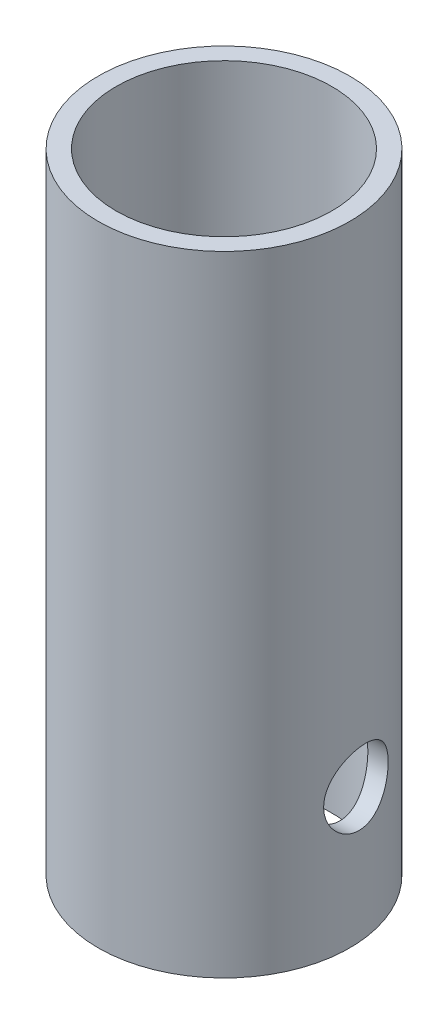
SolidWorks part; units mm, degrees
ref_plane "Спереди" through (0, 0, 0) normal (0, 0, 1) x (1, 0, 0)
ref_plane "Сверху" through (0, 0, 0) normal (0, 1, 0) x (1, 0, 0)
ref_plane "Справа" through (0, 0, 0) normal (1, 0, 0) x (0, 0, -1)
sketch "Эскиз1" plane through (0, 0, 0) normal (0, 1, 0) x (1, 0, 0)
  circle A0 centre (0, 0) radius 12
  circle A1 centre (0, 0) radius 14
  dimension "D1" = 24
  dimension "D2" = 28
extrude "Вытянуть1" add sketch "Эскиз1" along normal blind 70
sketch "Эскиз4" plane through (-28.8652, 0, 1.8021) normal (-0.9981, 0, 0.0623) x (0.0623, 0, 0.9981)
  circle A0 centre (-0.4881, 14.7483) radius 4
extrude "Вырез-Вытянуть2" cut sketch "Эскиз4" against normal blind 64
